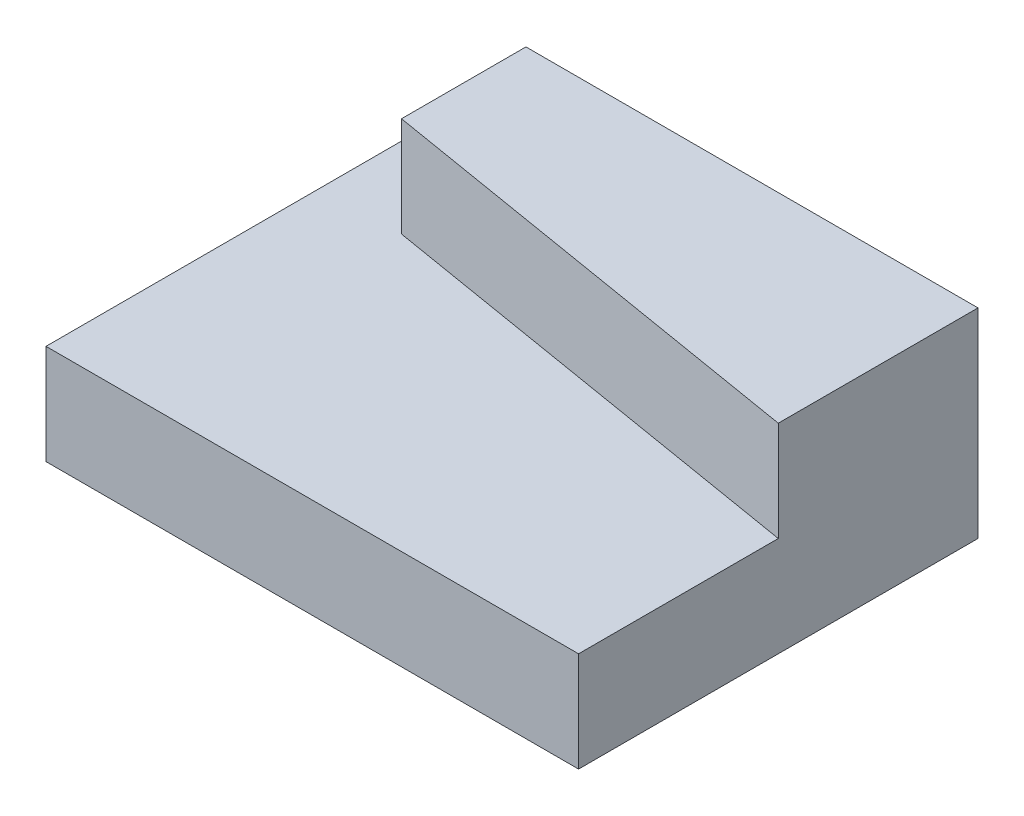
SolidWorks part; units mm, degrees
ref_plane "Front Plane" through (0, 0, 0) normal (0, 0, 1) x (1, 0, 0)
ref_plane "Top Plane" through (0, 0, 0) normal (0, 1, 0) x (1, 0, 0)
ref_plane "Right Plane" through (0, 0, 0) normal (1, 0, 0) x (0, 0, -1)
sketch "Sketch14" plane through (0, 0, 0) normal (0, 1, 0) x (1, 0, 0)
  line L1 (0, 0) -> (101.6, 0)
  line L2 (0, 0) -> (0, 76.2)
  line L3 (0, 76.2) -> (101.6, 76.2)
  line L4 (101.6, 0) -> (101.6, 76.2)
  dimension "D1" = 101.6
  dimension "D2" = 76.2
extrude "Extrude5" add sketch "Sketch14" against normal blind 19.05
sketch "Sketch15" plane through (0, 0, 0) normal (0, 1, 0) x (1, 0, 0)
  line L0 (101.6, 38.1) -> (15.3596, 52.4594)
  line L1 (101.6, 76.2) -> (15.3596, 76.2)
  line L2 (101.6, 76.2) -> (101.6, 38.1)
  line L4 (15.3596, 52.4594) -> (15.3596, 76.2)
extrude "Extrude6" add sketch "Sketch15" along normal blind 19.05
